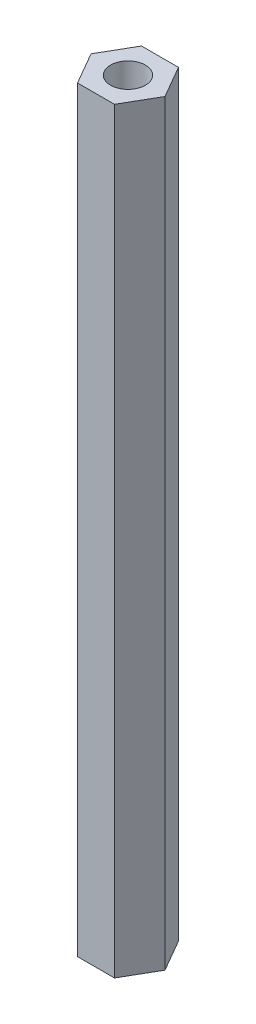
SolidWorks part; units mm, degrees
ref_plane "Front Plane" through (0, 0, 0) normal (0, 0, 1) x (1, 0, 0)
ref_plane "Top Plane" through (0, 0, 0) normal (0, 1, 0) x (1, 0, 0)
ref_plane "Right Plane" through (0, 0, 0) normal (1, 0, 0) x (0, 0, -1)
sketch "Sketch1" plane through (0, 0, 0) normal (0, 1, 0) x (1, 0, 0)
  line L1 (3.1754, 0) -> (1.5877, 2.75)
  line L2 (1.5877, 2.75) -> (-1.5877, 2.75)
  line L3 (-1.5877, 2.75) -> (-3.1754, 0)
  line L4 (-3.1754, 0) -> (-1.5877, -2.75)
  line L5 (-1.5877, -2.75) -> (1.5877, -2.75)
  line L6 (1.5877, -2.75) -> (3.1754, 0)
  circle A0 centre (0, 0) radius 2.75 construction
  dimension "D1" = 5.5
extrude "Boss-Extrude1" add sketch "Sketch1" along normal blind 65
sketch "Sketch2" plane through (0, 65, 0) normal (0, 1, 0) x (1, 0, 0)
  circle A0 centre (0, 0) radius 1.5
  dimension "D1" = 3
extrude "Cut-Extrude1" cut sketch "Sketch2" against normal blind 10
ref_plane "Plane1" through (0, 32.5, 0) normal (0, -1, 0) x (-1, 0, 0)
mirror "Mirror1" about plane through (0, 32.5, 0) normal (0, -1, 0) of "Cut-Extrude1"
